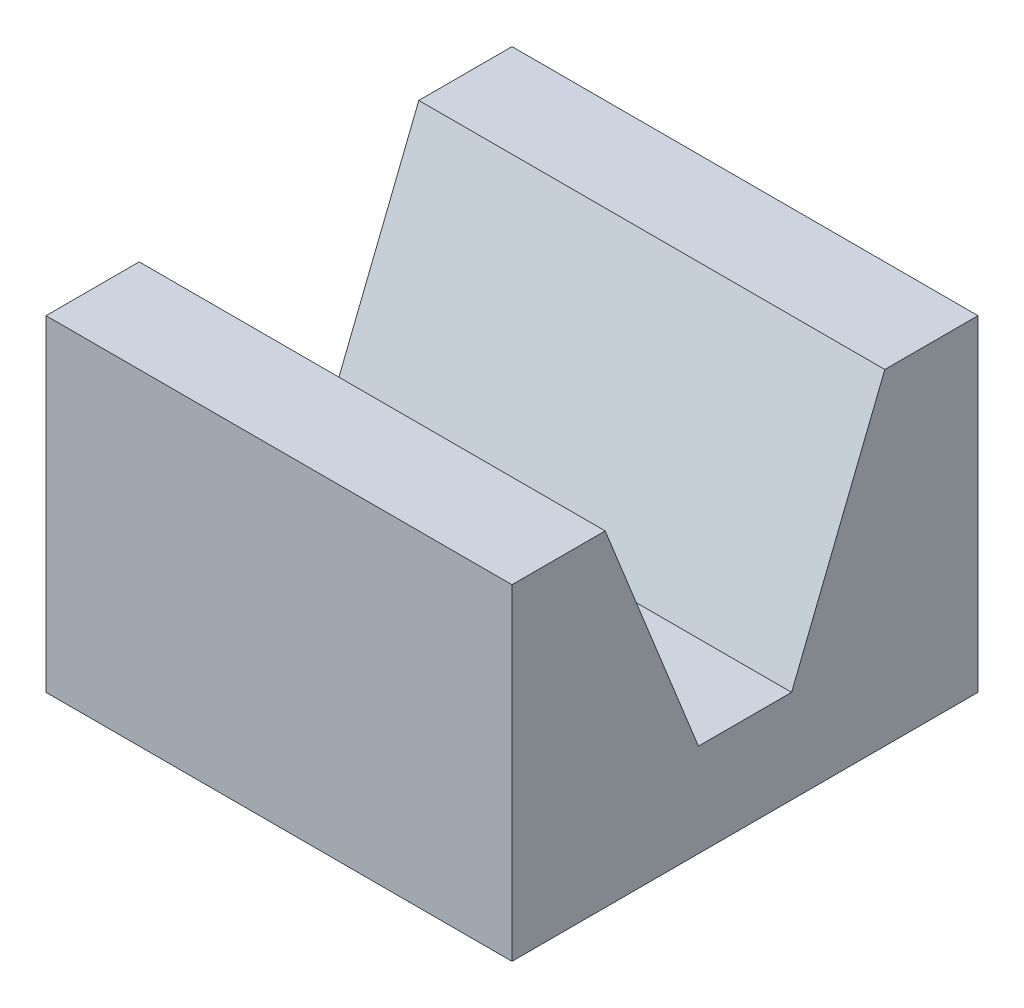
SolidWorks part; units mm, degrees
ref_plane "Front Plane" through (0, 0, 0) normal (0, 0, 1) x (1, 0, 0)
ref_plane "Top Plane" through (0, 0, 0) normal (0, 1, 0) x (1, 0, 0)
ref_plane "Right Plane" through (0, 0, 0) normal (1, 0, 0) x (0, 0, -1)
sketch "Sketch1" plane through (0, 0, 0) normal (1, 0, 0) x (0, 0, -1)
  line L1 (0, 0) -> (50, 0)
  line L2 (0, 0) -> (0, 70)
  line L3 (0, 70) -> (50, 70)
  line L4 (50, 0) -> (50, 70)
  dimension "D1" = 50
  dimension "D2" = 70
extrude "Boss-Extrude1" add sketch "Sketch1" along normal blind 100
sketch "Sketch2" plane through (100, 0, 0) normal (1, 0, 0) x (0, 0, -1)
  line L0 (0, 70) -> (30, 70)
  line L1 (50, 70) -> (0, 70) construction
  line L2 (30, 70) -> (10, 20)
  line L3 (10, 20) -> (0, 20)
  line L4 (0, 70) -> (0, 0) construction
  line L5 (0, 20) -> (0, 70)
  dimension "D1" = 10
  dimension "D2" = 50
  dimension "D3" = 30
extrude "Cut-Extrude1" cut sketch "Sketch2" against normal blind 100
mirror "Mirror1" about plane through (0, 0, 0) normal (0, 0, 1) of bodies 102
